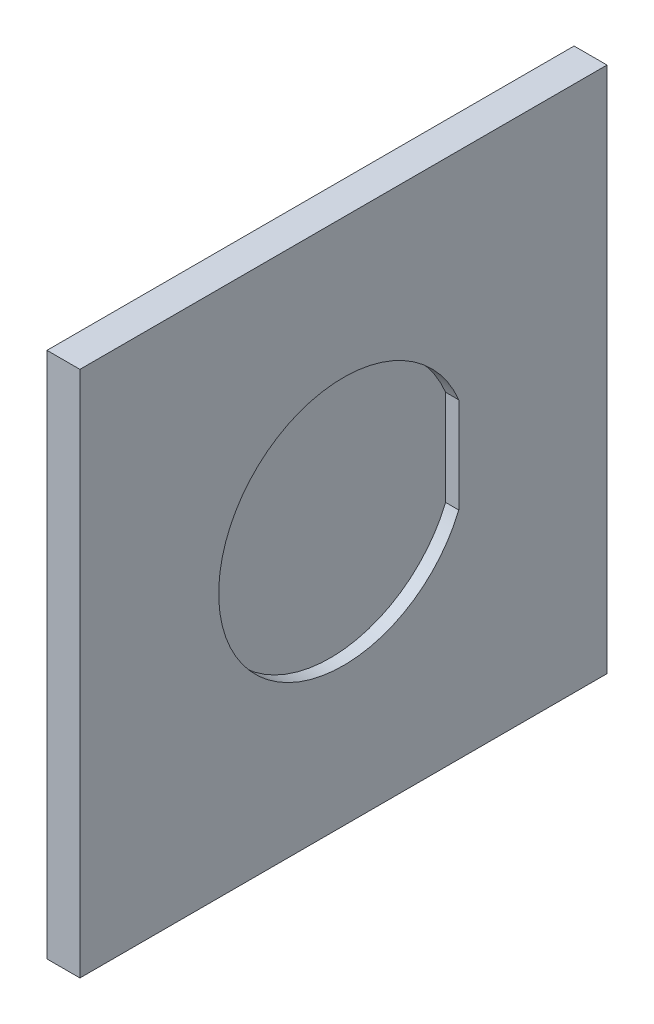
SolidWorks part; units mm, degrees
ref_plane "Front Plane" through (0, 0, 0) normal (0, 0, 1) x (1, 0, 0)
ref_plane "Top Plane" through (0, 0, 0) normal (0, 1, 0) x (1, 0, 0)
ref_plane "Right Plane" through (0, 0, 0) normal (1, 0, 0) x (0, 0, -1)
sketch "Sketch2" plane through (0, 0, 0) normal (1, 0, 0) x (0, 0, -1)
  line L1 (0, 0) -> (80, 0)
  line L2 (0, 0) -> (0, 80)
  line L3 (0, 80) -> (80, 80)
  line L4 (80, 0) -> (80, 80)
  dimension "D1" = 80
  dimension "D2" = 80
extrude "Boss-Extrude1" add sketch "Sketch2" along normal blind 5
sketch "Sketch3" plane through (5, 0, 0) normal (1, 0, 0) x (0, 0, -1)
  line L0 (57, 32.7589) -> (57, 47.2411)
  line L1 (0, 0) -> (80, 0) construction
  line L2 (80, 0) -> (80, 80) construction
  arc A0 (57, 47.2411) -> (57, 32.7589) centre (40, 40) ccw
  point P6 (40, 0)
  point P8 (80, 40)
  dimension "D1" = 0
  dimension "D2" = 0
  dimension "D3" = 14.4821
  dimension "D4" = 17
extrude "Boss-Extrude2" add sketch "Sketch3" along normal blind 1
sketch "Sketch4" plane through (6, 0, 0) normal (1, 0, 0) x (0, 0, -1)
  line L0 (57.5, 32.759) -> (57.5, 47.2411)
  line L1 (0, 0) -> (80, 0) construction
  line L2 (80, 0) -> (80, 80) construction
  arc A0 (57.5, 47.2411) -> (57.5, 32.759) centre (40, 40) ccw
  point P6 (40, 0)
  point P8 (80, 40)
  dimension "D4" = 17.5
  dimension "D1" = 0
  dimension "D2" = 0
  dimension "D3" = 0
extrude "Cut-Extrude1" cut sketch "Sketch4" against normal blind 3
